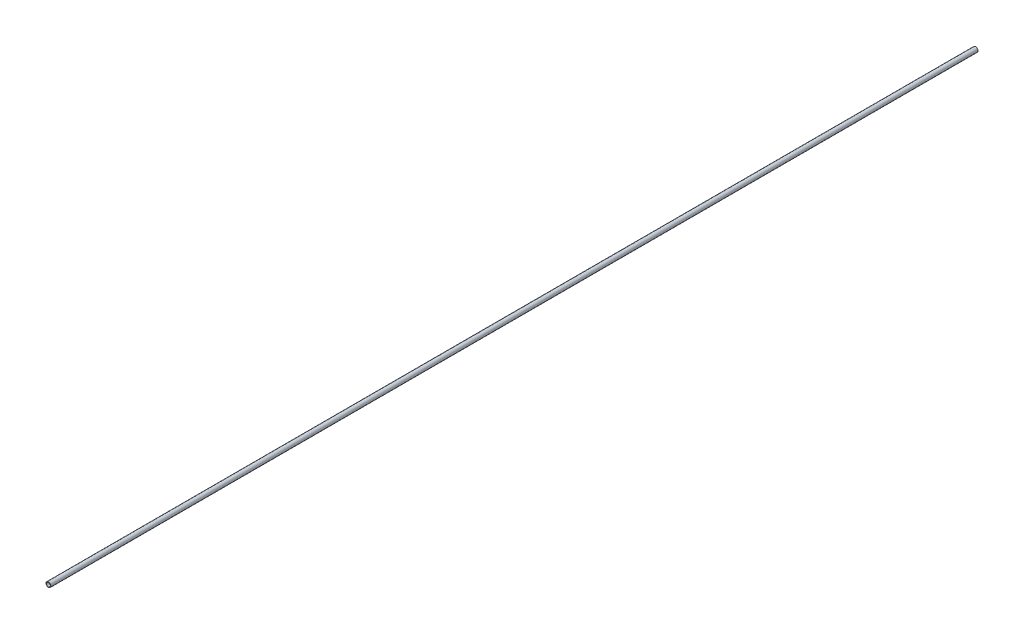
SolidWorks part; units mm, degrees
material "Cast Carbon Steel"
ref_plane "Front Plane" through (0, 0, 0) normal (0, 0, 1) x (1, 0, 0)
ref_plane "Top Plane" through (0, 0, 0) normal (0, 1, 0) x (1, 0, 0)
ref_plane "Right Plane" through (0, 0, 0) normal (1, 0, 0) x (0, 0, -1)
sketch "Sketch1" plane through (0, 0, 0) normal (0, 0, 1) x (1, 0, 0)
  circle A0 centre (0, 0) radius 13.3223
  circle A1 centre (0, 0) radius 16.7005
extrude "Boss-Extrude1" add sketch "Sketch1" against normal blind 6426.2
